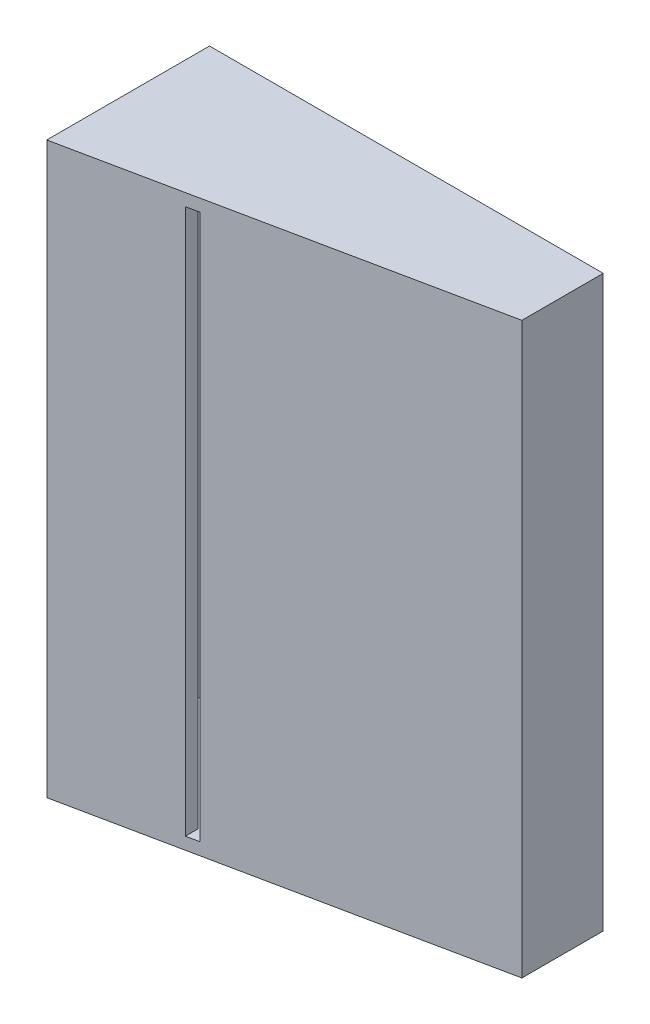
SolidWorks part; units mm, degrees
ref_plane "Front Plane" through (0, 0, 0) normal (0, 0, 1) x (1, 0, 0)
ref_plane "Top Plane" through (0, 0, 0) normal (0, 1, 0) x (1, 0, 0)
ref_plane "Right Plane" through (0, 0, 0) normal (1, 0, 0) x (0, 0, -1)
sketch "Sketch1" plane through (0, 0, 0) normal (0, 0, 1) x (1, 0, 0)
  line L3 (-46.8875, 15.35) -> (-46.8875, 35.15)
  line L6 (-46.8875, 35.15) -> (-43.9875, 35.15)
  line L7 (-43.9875, 15.35) -> (-46.8875, 15.35)
  line L8 (-43.9875, 35.15) -> (-43.9875, 15.35)
  line L9 (-46.8875, 35.15) -> (-43.9875, 35.15)
  line L10 (-43.9875, 15.35) -> (-46.8875, 15.35)
  line L11 (-43.9875, 35.15) -> (-43.9875, 15.35)
  dimension "D1" = 0.1
extrude "Boss-Extrude1" add sketch "Sketch1" against normal up to surface (1.5 mm away)
sketch "Sketch2" plane through (0, 0, -1.5) normal (0, 0, -1) x (-1, 0, 0)
  line L0 (24.3875, 19.15) -> (24.3875, 31.35) construction
  line L1 (46.8875, 12.35) -> (24.3875, 12.35)
  line L2 (46.8875, 12.35) -> (46.8875, 38.15)
  line L3 (46.8875, 38.15) -> (24.3875, 38.15)
  line L4 (24.3875, 12.35) -> (24.3875, 38.15)
  line L5 (46.8875, 12.35) -> (24.3875, 38.15) construction
  line L6 (46.8875, 38.15) -> (24.3875, 12.35) construction
  line L12 (24.3875, 25.25) -> (46.8875, 25.25) construction
  line L13 (46.8875, 35.15) -> (46.8875, 15.35) construction
  line L14 (46.8875, -9.75) -> (46.8875, 60.25) construction
  line L16 (43.9875, 35.15) -> (46.8875, 35.15) construction
  point P0 (35.6375, 25.25)
  dimension "D1" = 3
extrude "Boss-Extrude3" add sketch "Sketch2" along normal blind 1.5
sketch "Sketch3" plane through (0, 0, 0) normal (0, 0, 1) x (1, 0, 0)
  line L0 (-46.8875, 15.25) -> (-46.8875, 35.25)
  line L8 (-43.8875, 35.25) -> (-43.8875, 15.25)
  line L9 (-43.8875, 15.25) -> (-46.8875, 15.25)
  line L10 (-46.8875, 15.25) -> (-46.8875, -9.75)
  line L11 (-46.8875, -9.75) -> (1.5, -9.75)
  line L12 (1.5, -9.75) -> (1.5, 60.25)
  line L13 (1.5, 60.25) -> (-46.8875, 60.25)
  line L14 (-46.8875, 60.25) -> (-46.8875, 35.25)
  line L15 (-46.8875, 35.25) -> (-43.8875, 35.25)
  line L18 (-46.8875, 15.25) -> (-46.8875, -9.75)
  line L19 (-46.8875, -9.75) -> (1.5, -9.75)
  line L20 (1.5, -9.75) -> (1.5, 60.25)
  line L21 (1.5, 60.25) -> (-46.8875, 60.25)
  line L22 (-46.8875, 60.25) -> (-46.8875, 35.25)
  dimension "D1" = 0
extrude "Boss-Extrude4" add sketch "Sketch3" along normal blind 20
sketch "Sketch4" plane through (0, -9.75, 0) normal (0, -1, 0) x (1, 0, 0)
  line L0 (-46.8875, 20) -> (1.5, 10)
  line L1 (1.5, 10) -> (1.5, 20)
  line L2 (1.5, 20) -> (-46.8875, 20)
  line L3 (1.5, 20) -> (1.5, 0) construction
  dimension "D1" = 10
extrude "Cut-Extrude1" cut sketch "Sketch4" against normal up to surface (70 mm away) up to face at (-22.6937, 60.25, 10)
ref_plane "Plane1" through (0, 25.25, 0) normal (0, 1, 0) x (1, 0, 0)
sketch "Sketch5" plane through (0, -9.75, 0) normal (0, -1, 0) x (1, 0, 0)
  line L4 (-46.8875, 20) -> (-46.8875, 0) construction
  line L8 (0, 1.5) -> (0, 8.7783)
  line L9 (0, 8.7783) -> (-45.3875, 18.1583)
  line L10 (-45.3875, 18.1583) -> (-45.3875, 1.5)
  line L11 (-45.3875, 1.5) -> (0, 1.5)
  line L12 (0, 1.5) -> (0, 8.7783)
  line L13 (0, 8.7783) -> (-46.8875, 18.4683)
  line L14 (-46.8875, 18.4683) -> (-46.8875, 1.5)
  line L15 (-46.8875, 1.5) -> (0, 1.5)
  dimension "D1" = 1.5
extrude "Cut-Extrude2" cut sketch "Sketch5" along normal up to surface (33.5 mm away) from offset 1.5
mirror "Mirror1" about plane through (0, 25.25, 0) normal (0, 1, 0) of "Cut-Extrude2"
sketch "Sketch6" plane through (0, 0, 0) normal (0, 0, -1) x (-1, 0, 0)
  line L0 (11, 25.25) -> (-11, 25.25) construction
  line L1 (32.77, 58.75) -> (31.27, 58.75)
  line L2 (32.77, 58.75) -> (32.77, -8.25)
  line L3 (32.77, -8.25) -> (31.27, -8.25)
  line L4 (31.27, 58.75) -> (31.27, -8.25)
  line L5 (32.77, 58.75) -> (31.27, -8.25) construction
  line L6 (32.77, -8.25) -> (31.27, 58.75) construction
  line L8 (46.8875, 58.75) -> (0, 58.75) construction
  line L9 (0, 58.75) -> (0, -8.25) construction
  point P0 (32.02, 25.25)
  dimension "D1" = 1.5
  dimension "D2" = 31.27
extrude "Cut-Extrude3" cut sketch "Sketch6" against normal up to surface (17.0824 mm away)
